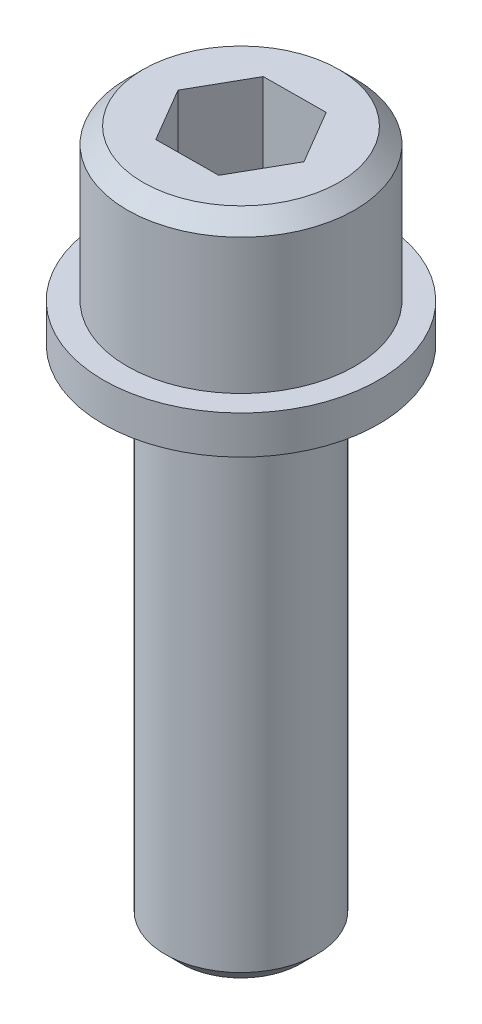
SolidWorks part; units mm, degrees
ref_plane "Front Plane" through (0, 0, 0) normal (0, 0, 1) x (1, 0, 0)
ref_plane "Top Plane" through (0, 0, 0) normal (0, 1, 0) x (1, 0, 0)
ref_plane "Right Plane" through (0, 0, 0) normal (1, 0, 0) x (0, 0, -1)
sketch "Sketch1" plane through (0, 0, 0) normal (0, 1, 0) x (1, 0, 0)
  circle A0 centre (0, 0) radius 8.65
  dimension "D1" = 17.3
extrude "Boss-Extrude1" add sketch "Sketch1" along normal blind 2.4
sketch "Sketch2" plane through (0, 2.4, 0) normal (0, 1, 0) x (1, 0, 0)
  circle A0 centre (0, 0) radius 7.15
  circle A1 centre (0, 0) radius 8.65 construction
  dimension "D1" = 14.3
extrude "Boss-Extrude2" add sketch "Sketch2" along normal blind 9.5
fillet "Chamfer2" radius 1 1 edges at (0, 11.9, 7.15) profile chamfer
sketch "Sketch3" plane through (0, 11.9, 0) normal (0, 1, 0) x (1, 0, 0)
  line L1 (-1.9879, 3.3855) -> (-3.9259, -0.0288)
  line L2 (-3.9259, -0.0288) -> (-1.938, -3.4143)
  line L3 (-1.938, -3.4143) -> (1.9879, -3.3855)
  line L4 (1.9879, -3.3855) -> (3.9259, 0.0288)
  line L5 (3.9259, 0.0288) -> (1.938, 3.4143)
  line L6 (1.938, 3.4143) -> (-1.9879, 3.3855)
  circle A0 centre (0, 0) radius 3.4 construction
  dimension "D1" = 6.8
extrude "Cut-Extrude1" cut sketch "Sketch3" against normal blind 6.4
sketch "Sketch4" plane through (0, 0, 0) normal (0, -1, 0) x (1, 0, 0)
  circle A0 centre (0, 0) radius 4.75
  dimension "D1" = 9.5
extrude "Boss-Extrude3" add sketch "Sketch4" along normal blind 31.8
chamfer "Chamfer3" distance 1 angle 45 1 edges at (0, -31.8, -4.75)
